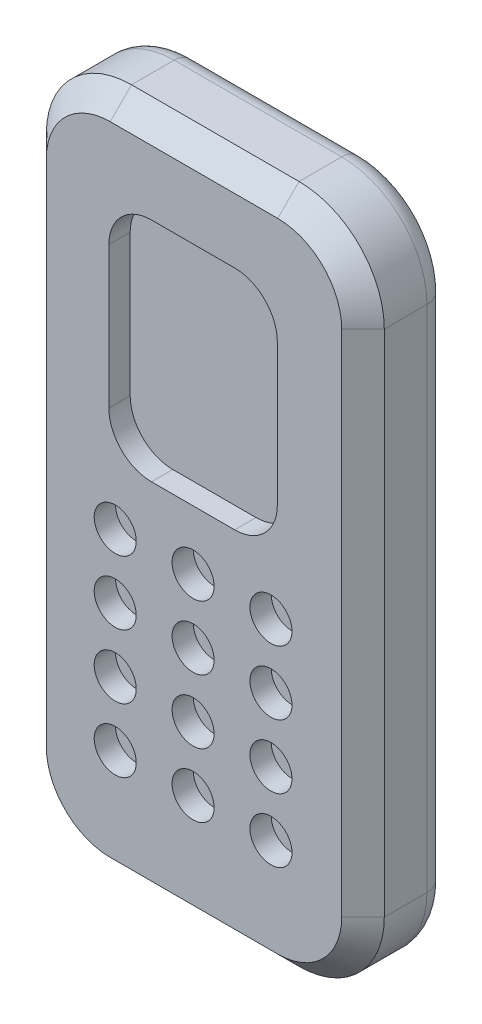
SolidWorks part; units mm, degrees
material "Acrylic (Medium-high impact)"
ref_plane "Front Plane" through (0, 0, 0) normal (0, 0, 1) x (1, 0, 0)
ref_plane "Top Plane" through (0, 0, 0) normal (0, 1, 0) x (1, 0, 0)
ref_plane "Right Plane" through (0, 0, 0) normal (1, 0, 0) x (0, 0, -1)
sketch "Sketch1" plane through (0, 0, 0) normal (0, 0, 1) x (1, 0, 0)
  line L1 (10.16, 0) -> (30.13, 0)
  line L2 (0, 10.16) -> (0, 70.8699)
  line L3 (10.16, 81.0299) -> (30.13, 81.0299)
  line L4 (40.29, 10.16) -> (40.29, 70.8699)
  arc A0 (10.16, 81.0299) -> (0, 70.8699) centre (10.16, 70.8699) ccw
  arc A1 (40.29, 70.8699) -> (30.13, 81.0299) centre (30.13, 70.8699) ccw
  arc A2 (30.13, 0) -> (40.29, 10.16) centre (30.13, 10.16) ccw
  arc A3 (10.16, 0) -> (0, 10.16) centre (10.16, 10.16) cw
  point P13 (0, 0)
  dimension "D1" = 10.16
extrude "Extrude1" add sketch "Sketch1" along normal blind 10.16
chamfer "Chamfer1" distance 2.54 angle 45 8 edges at (20.145, 0, 10.16) (37.3142, 2.9758, 10.16) (2.9758, 2.9758, 10.16) (40.29, 40.515, 10.16) (0, 40.515, 10.16) (37.3142, 78.0541, 10.16) (2.9758, 78.0541, 10.16) (20.145, 81.0299, 10.16)
fillet "Fillet1" radius 2.54 8 edges at (37.3142, 2.9758, 0) (20.145, 0, 0) (2.9758, 2.9758, 0) (0, 40.515, 0) (2.9758, 78.0541, 0) (20.145, 81.0299, 0) (37.3142, 78.0541, 0) (40.29, 40.515, 0)
sketch "Sketch2" plane through (0, 0, 10.16) normal (0, 0, 1) x (1, 0, 0)
  line L1 (9.995, 70.8022) -> (30.0779, 70.8022)
  line L2 (9.995, 70.8022) -> (9.995, 43.7717)
  line L3 (9.995, 43.7717) -> (30.0779, 43.7717)
  line L4 (30.0779, 70.8022) -> (30.0779, 43.7717)
  circle A0 centre (10.7549, 36.7155) radius 2.5062
  circle A1 centre (20.0365, 36.7155) radius 2.5062
  circle A2 centre (29.318, 36.7155) radius 2.5062
  circle A3 centre (10.7549, 29.0955) radius 2.5062
  circle A4 centre (20.0365, 29.0955) radius 2.5062
  circle A5 centre (29.318, 29.0955) radius 2.5062
  circle A6 centre (10.7549, 21.4755) radius 2.5062
  circle A7 centre (20.0365, 21.4755) radius 2.5062
  circle A8 centre (29.318, 21.4755) radius 2.5062
  circle A9 centre (10.7549, 13.8555) radius 2.5062
  circle A10 centre (20.0365, 13.8555) radius 2.5062
  circle A11 centre (29.318, 13.8555) radius 2.5062
extrude "Extrude2" cut sketch "Sketch2" against normal blind 2.54
fillet "Fillet2" radius 5.08 4 edges at (9.995, 70.8022, 8.89) (30.0779, 70.8022, 8.89) (30.0779, 43.7717, 8.89) (9.995, 43.7717, 8.89)
sketch "Sketch3" plane through (0, 0, 10.16) normal (0, 0, 1) x (1, 0, 0)
  line L0 (5.4188, 1.4444) -> (15.9608, 24.3759) construction
ref_plane "Plane1" through (5.4188, 1.4444, 10.16) normal (0.4177, 0.9086, 0) x (-0.9086, 0.4177, 0)
